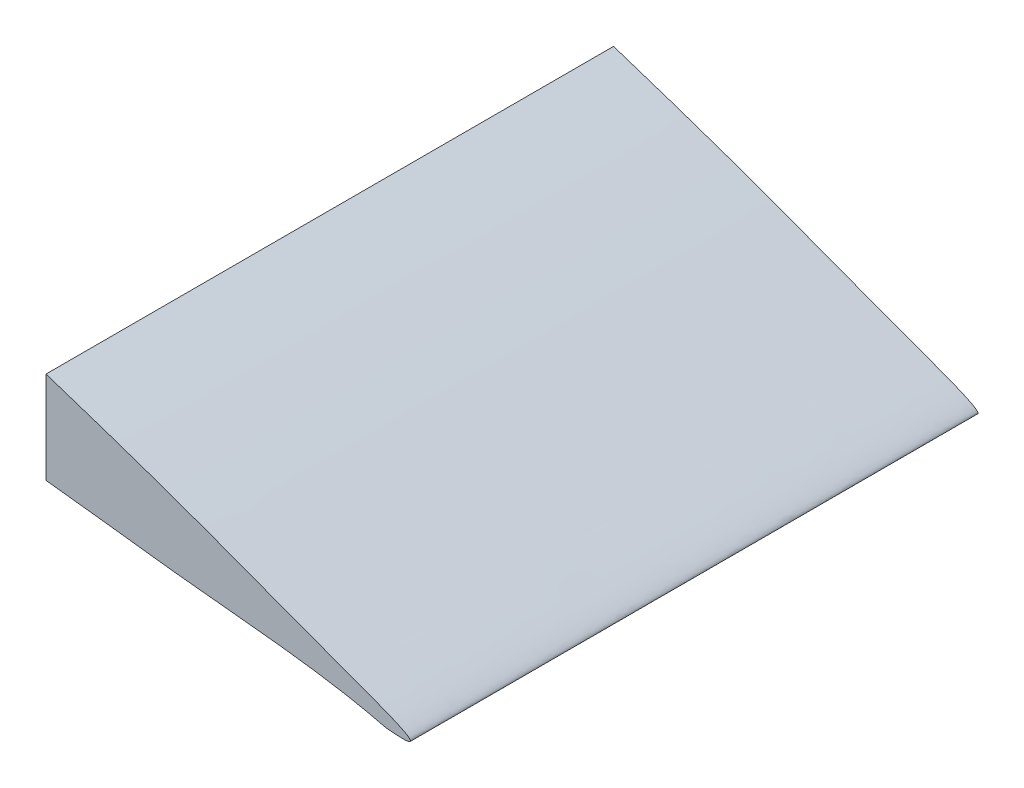
SolidWorks part; units mm, degrees
ref_plane "Front Plane" through (0, 0, 0) normal (0, 0, 1) x (1, 0, 0)
ref_plane "Top Plane" through (0, 0, 0) normal (0, 1, 0) x (1, 0, 0)
ref_plane "Right Plane" through (0, 0, 0) normal (1, 0, 0) x (0, 0, -1)
sketch "Sketch1" plane through (0, 0, 0) normal (0, 0, 1) x (1, 0, 0)
  spline S0 degree 3 poles (0.0006, 0.0001) (0.8106, 7.3592) (8.6491, 17.8566) (26.2867, 29.9752) (52.1111, 42.0692) (89.5976, 49.2908) (131.4008, 47.8848) (173.2567, 40.0411) (217.9611, 29.613) (256.9521, 19.5289) (290.3598, 8.711) (301.2732, 4.3828) (314.8169, -0.5162) (309.8463, 0.0001) knots 0 0 0 0 0.060864 0.113688 0.188609 0.312909 0.448482 0.557612 0.691544 0.852438 0.929756 0.976058 1 1 1 1
  spline S1 degree 3 poles (309.8463, 0.0001) (303.9568, 1.471) (293.9895, 2.094) (276.264, 4.5144) (260.8463, 5.4274) (235.8588, 7.8703) (205.1014, 8.8381) (157.7186, 9.0307) (110.4973, 6.1815) (66.5062, -0.5867) (36.4547, -6.0985) (15.3166, -6.1891) (1.2307, -6.9241) (0.0006, 0.0001) knots 0 0 0 0 0.057787 0.095275 0.171021 0.205339 0.335319 0.464904 0.658702 0.785512 0.893517 0.943092 1 1 1 1
extrude "Boss-Extrude1" add sketch "Sketch1" along normal blind 50.8
sketch "Sketch2" plane through (0, 0, 50.8) normal (0, 0, 1) x (1, 0, 0)
  circle A0 centre (20.32, 10.16) radius 6.35
  circle A1 centre (227.2963, 19.0501) radius 3.175
  dimension "D2" = 12.7
  dimension "D3" = 6.35
  dimension "D6" = 20.32
  dimension "D1" = 82.55
  dimension "D4" = 19.05
  dimension "D5" = 10.16
extrude "Cut-Extrude1" cut sketch "Sketch2" against normal through all
sketch "Sketch4" plane through (0, 0, 50.8) normal (0, 0, 1) x (1, 0, 0)
  line L1 (279.4, -24.2166) -> (-11.5456, -24.2166)
  line L2 (279.4, -24.2166) -> (279.4, 93.2727)
  line L3 (279.4, 93.2727) -> (-11.5456, 93.2727)
  line L4 (-11.5456, -24.2166) -> (-11.5456, 93.2727)
  dimension "D1" = 279.4
extrude "Cut-Extrude3" cut sketch "Sketch4" against normal through all
